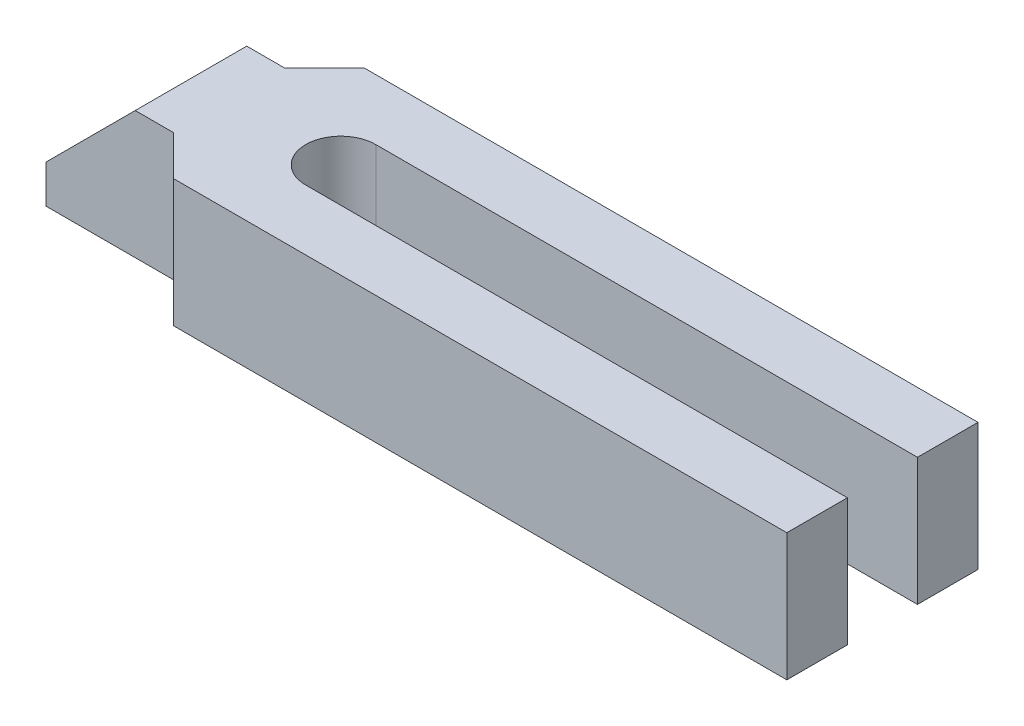
SolidWorks part; units mm, degrees
ref_plane "Front Plane" through (0, 0, 0) normal (0, 0, 1) x (1, 0, 0)
ref_plane "Top Plane" through (0, 0, 0) normal (0, 1, 0) x (1, 0, 0)
ref_plane "Right Plane" through (0, 0, 0) normal (1, 0, 0) x (0, 0, -1)
sketch "Sketch1" plane through (0, 0, 0) normal (0, 1, 0) x (1, 0, 0)
  line L0 (0, 0) -> (0, 17.5)
  line L1 (0, 17.5) -> (40, 17.5)
  line L2 (40, 17.5) -> (52.5, 30)
  line L3 (52.5, 30) -> (245, 30)
  line L4 (245, 30) -> (245, 11)
  line L5 (245, 11) -> (75, 11)
  line L7 (75, -11) -> (245, -11)
  line L8 (245, -11) -> (245, -30)
  line L9 (245, -30) -> (52.5, -30)
  line L10 (52.5, -30) -> (40, -17.5)
  line L11 (40, -17.5) -> (0, -17.5)
  line L12 (0, -17.5) -> (0, 0)
  line L13 (0, 0) -> (245, 0) construction
  arc A0 (75, -11) -> (75, 11) centre (75, 0) cw
  dimension "D7" = 170
  dimension "D1" = 35
  dimension "D2" = 60
  dimension "D3" = 245
  dimension "D4" = 40
  dimension "D5" = 45
  dimension "D6" = 22
extrude "Boss-Extrude1" add sketch "Sketch1" along normal blind 40 contours L1 L2 L3 L4 L5 A0 L7 L8 L9 L10 L11 L12 L0
chamfer "Chamfer1" distance 28 angle 45 1 edges at (0, 40, 0)
